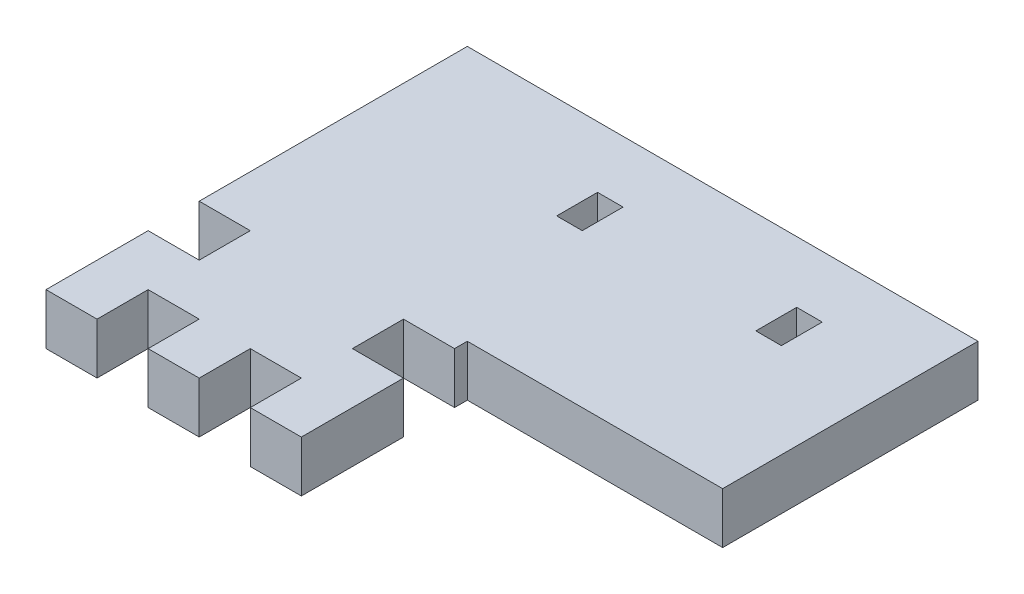
SolidWorks part; units mm, degrees
ref_plane "Front Plane" through (0, 0, 0) normal (0, 0, 1) x (1, 0, 0)
ref_plane "Top Plane" through (0, 0, 0) normal (0, 1, 0) x (1, 0, 0)
ref_plane "Right Plane" through (0, 0, 0) normal (1, 0, 0) x (0, 0, -1)
sketch "Sketch1" plane through (0, 0, 0) normal (0, 1, 0) x (1, 0, 0)
  line L0 (0, 0) -> (0, 20.955)
  line L1 (0, 20.955) -> (25.4, 20.955)
  line L2 (25.4, 20.955) -> (25.4, 8.255)
  line L3 (25.4, 8.255) -> (12.7, 8.255)
  line L4 (12.7, 8.255) -> (12.7, 0)
  line L5 (12.7, 0) -> (0, 0)
  dimension "D1" = 12.7
  dimension "D2" = 12.7
  dimension "D3" = 20.955
  dimension "D4" = 25.4
extrude "Boss-Extrude1" add sketch "Sketch1" along normal blind 2.54
sketch "Sketch2" plane through (0, 2.54, 0) normal (0, 1, 0) x (1, 0, 0)
  line L0 (0, 0) -> (12.7, 0) construction
  line L1 (2.54, 0) -> (5.08, 0)
  line L2 (2.54, 0) -> (2.54, 2.54)
  line L3 (2.54, 2.54) -> (5.08, 2.54)
  line L4 (5.08, 0) -> (5.08, 2.54)
  line L5 (12.7, 0) -> (12.7, 8.255) construction
  line L6 (7.62, 0) -> (10.16, 0)
  line L7 (7.62, 0) -> (7.62, 2.54)
  line L8 (7.62, 2.54) -> (10.16, 2.54)
  line L9 (10.16, 0) -> (10.16, 2.54)
  dimension "D1" = 2.54
  dimension "D2" = 2.54
  dimension "D3" = 2.54
  dimension "D4" = 2.54
extrude "Cut-Extrude1" cut sketch "Sketch2" against normal through all
sketch "Sketch3" plane through (0, 2.54, 0) normal (0, 1, 0) x (1, 0, 0)
  line L0 (0, 20.955) -> (0, 0) construction
  line L1 (9.525, 15.875) -> (10.795, 15.875)
  line L2 (9.525, 15.875) -> (9.525, 17.907)
  line L3 (9.525, 17.907) -> (10.795, 17.907)
  line L4 (10.795, 15.875) -> (10.795, 17.907)
  line L6 (10.16, 0) -> (12.7, 0) construction
  line L7 (19.431, 15.875) -> (20.701, 15.875)
  line L8 (19.431, 15.875) -> (19.431, 17.907)
  line L9 (19.431, 17.907) -> (20.701, 17.907)
  line L10 (20.701, 15.875) -> (20.701, 17.907)
  dimension "D1" = 9.525
  dimension "D2" = 15.875
  dimension "D3" = 2.032
  dimension "D4" = 1.27
  dimension "D5" = 2.032
  dimension "D6" = 1.27
  dimension "D7" = 11.176
extrude "Cut-Extrude2" cut sketch "Sketch3" against normal through all
sketch "Sketch4" plane through (0, 2.54, 0) normal (0, 1, 0) x (1, 0, 0)
  line L0 (0, 20.955) -> (0, 0) construction
  line L1 (0, 7.62) -> (2.54, 7.62)
  line L2 (0, 7.62) -> (0, 5.08)
  line L3 (0, 5.08) -> (2.54, 5.08)
  line L4 (2.54, 7.62) -> (2.54, 5.08)
  line L5 (12.7, 0) -> (12.7, 8.255) construction
  line L6 (12.7, 7.62) -> (10.16, 7.62)
  line L7 (12.7, 7.62) -> (12.7, 5.08)
  line L8 (12.7, 5.08) -> (10.16, 5.08)
  line L9 (10.16, 7.62) -> (10.16, 5.08)
  line L10 (0, 0) -> (2.54, 0) construction
  dimension "D1" = 2.54
  dimension "D2" = 5.08
extrude "Cut-Extrude3" cut sketch "Sketch4" against normal through all
